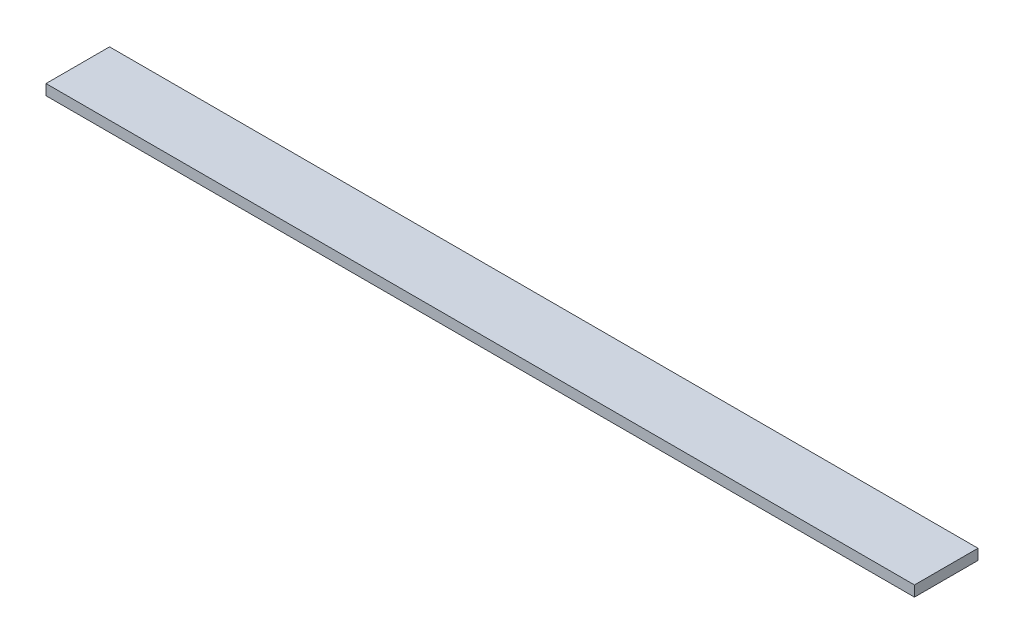
SolidWorks part; units mm, degrees
ref_plane "Front Plane" through (0, 0, 0) normal (0, 0, 1) x (1, 0, 0)
ref_plane "Top Plane" through (0, 0, 0) normal (0, 1, 0) x (1, 0, 0)
ref_plane "Right Plane" through (0, 0, 0) normal (1, 0, 0) x (0, 0, -1)
sketch "Sketch1" plane through (0, 0, 0) normal (0, 1, 0) x (1, 0, 0)
  line L1 (0, 0) -> (260.35, 0)
  line L2 (0, 0) -> (0, 19.05)
  line L3 (0, 19.05) -> (260.35, 19.05)
  line L4 (260.35, 0) -> (260.35, 19.05)
  dimension "D1" = 260.35
  dimension "D2" = 19.05
extrude "Boss-Extrude1" add sketch "Sketch1" along normal blind 3.175
